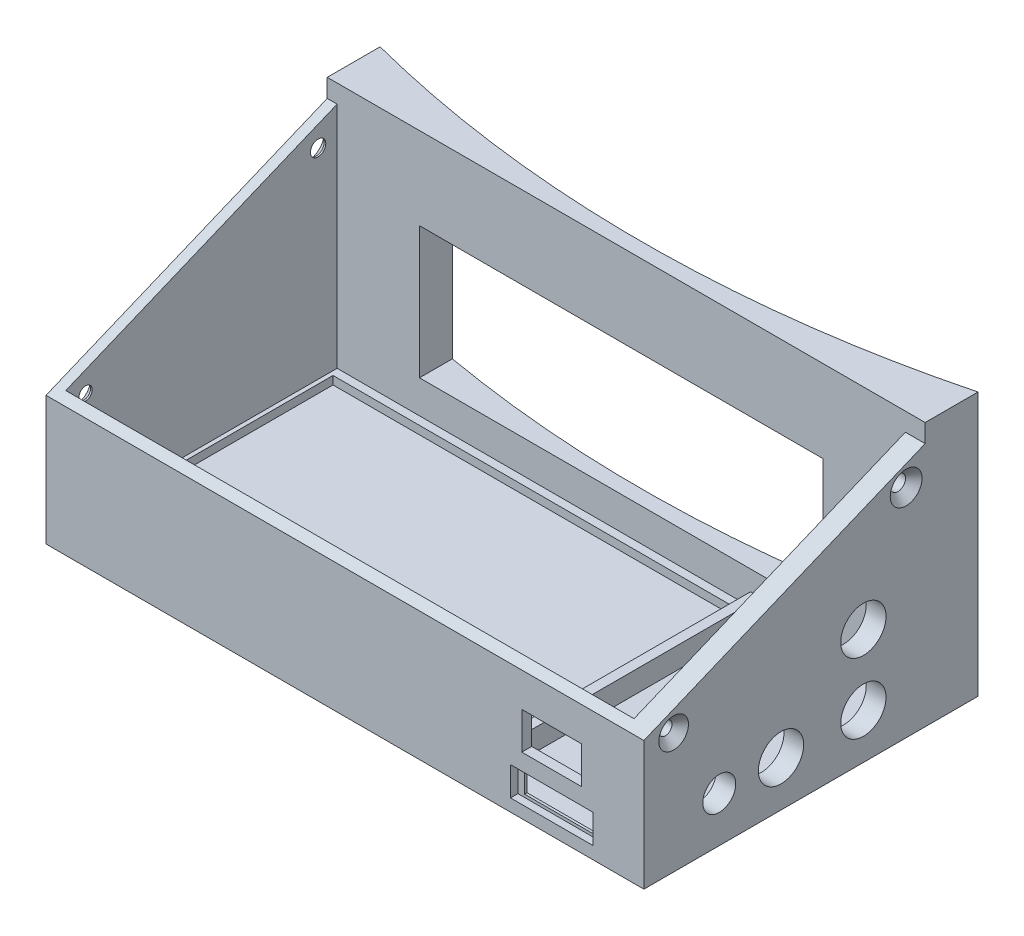
SolidWorks part; units mm, degrees
ref_plane "Ebene vorne" through (0, 0, 0) normal (0, 0, 1) x (1, 0, 0)
ref_plane "Ebene oben" through (0, 0, 0) normal (0, 1, 0) x (1, 0, 0)
ref_plane "Ebene rechts" through (0, 0, 0) normal (1, 0, 0) x (0, 0, -1)
sketch "Skizze1" plane through (0, 0, 0) normal (0, 1, 0) x (1, 0, 0)
  line L1 (0, 0) -> (145.2, 0)
  line L2 (0, 0) -> (0, 70.7)
  line L3 (0, 70.7) -> (145.2, 70.7)
  line L4 (145.2, 0) -> (145.2, 70.7)
  line L5 (0, 0) -> (145.2, 70.7) construction
  line L6 (0, 70.7) -> (145.2, 0) construction
  point P4 (72.6, 35.35)
  dimension "D1" = 145.2
  dimension "D2" = 70.7
extrude "Aufsatz-Linear austragen1" add sketch "Skizze1" along normal blind 64
sketch "Skizze3" plane through (0, 0, 0) normal (0, -1, 0) x (1, 0, 0)
  line L0 (0, -70.7) -> (145.2, -70.7)
  line L1 (145.2, -70.7) -> (145.2, -81.1345)
  line L2 (0, -70.7) -> (0, -81.1345)
  arc A0 (0, -81.1345) -> (145.2, -81.1345) centre (72.6, -361.9) cw
  point P8 (72.6, -71.9)
  point P10 (72.6, -70.7)
  dimension "D1" = 290
  dimension "D2" = 1.2
extrude "Aufsatz-Linear austragen2" add sketch "Skizze3" against normal up to vertex (64 mm away) up to point (145.2, 64, -70.7)
sketch "Skizze4" plane through (0, 0, 0) normal (0, -1, 0) x (1, 0, 0)
  line L0 (0, 0) -> (145.2, 0) construction
  line L1 (102.8, -2.4) -> (2.4, -2.4)
  line L2 (102.8, -2.4) -> (102.8, -68.3)
  line L3 (102.8, -68.3) -> (2.4, -68.3)
  line L4 (2.4, -2.4) -> (2.4, -68.3)
  line L5 (102.8, -2.4) -> (2.4, -68.3) construction
  line L6 (102.8, -68.3) -> (2.4, -2.4) construction
  line L8 (0, -81.1345) -> (0, 0) construction
  line L9 (145.2, 0) -> (145.2, -81.1345) construction
  line L10 (105.2, -2.4) -> (140.4, -2.4)
  line L11 (105.2, -2.4) -> (105.2, -68.3)
  line L12 (105.2, -68.3) -> (140.4, -68.3)
  line L13 (140.4, -2.4) -> (140.4, -68.3)
  line L14 (105.2, -2.4) -> (140.4, -68.3) construction
  line L15 (105.2, -68.3) -> (140.4, -2.4) construction
  point P4 (52.6, -35.35)
  point P13 (122.8, -35.35)
  dimension "D1" = 2.4
  dimension "D2" = 2.4
  dimension "D3" = 100.4
  dimension "D4" = 65.9
  dimension "D5" = 2.4
  dimension "D6" = 4.8
extrude "Schnitt-Linear austragen3" cut sketch "Skizze4" against normal through all
sketch "Skizze5" plane through (0, 0, 0) normal (0, -1, 0) x (1, 0, 0)
  line L1 (2.4, -2.4) -> (102.8, -2.4)
  line L2 (2.4, -2.4) -> (2.4, -68.3)
  line L3 (2.4, -68.3) -> (102.8, -68.3)
  line L4 (102.8, -2.4) -> (102.8, -68.3)
  line L5 (2.4, -2.4) -> (102.8, -68.3) construction
  line L6 (2.4, -68.3) -> (102.8, -2.4) construction
  line L7 (105.2, -2.4) -> (140.4, -2.4)
  line L8 (105.2, -2.4) -> (105.2, -68.3)
  line L9 (105.2, -68.3) -> (140.4, -68.3)
  line L10 (140.4, -2.4) -> (140.4, -68.3)
  line L11 (105.2, -2.4) -> (140.4, -68.3) construction
  line L12 (105.2, -68.3) -> (140.4, -2.4) construction
  point P4 (52.6, -35.35)
  point P11 (122.8, -35.35)
extrude "Aufsatz-Linear austragen3" add sketch "Skizze5" against normal blind 2 separate body
sketch "Skizze6" plane through (0, 2, 0) normal (0, 1, 0) x (1, 0, 0)
  line L1 (2.4, 68.3) -> (102.8, 68.3)
  line L2 (2.4, 68.3) -> (2.4, 2.4)
  line L3 (2.4, 2.4) -> (102.8, 2.4)
  line L4 (102.8, 68.3) -> (102.8, 2.4)
  line L5 (2.4, 68.3) -> (102.8, 2.4) construction
  line L6 (2.4, 2.4) -> (102.8, 68.3) construction
  line L7 (3.4, 66.3) -> (101.8, 66.3)
  line L8 (3.4, 66.3) -> (3.4, 4.4)
  line L9 (3.4, 4.4) -> (101.8, 4.4)
  line L10 (101.8, 66.3) -> (101.8, 4.4)
  line L11 (3.4, 66.3) -> (101.8, 4.4) construction
  line L12 (3.4, 4.4) -> (101.8, 66.3) construction
  point P4 (52.6, 35.35)
  point P11 (52.6, 35.35)
  dimension "D1" = 2
  dimension "D2" = 2
  dimension "D3" = 1
  dimension "D4" = 1
extrude "Aufsatz-Linear austragen4" add sketch "Skizze6" along normal blind 2
sketch "Skizze8" plane through (0, 64, 0) normal (0, 1, 0) x (1, 0, 0)
  line L1 (102.8, 68.3) -> (105.2, 68.3)
  line L2 (102.8, 68.3) -> (102.8, 2.4)
  line L3 (102.8, 2.4) -> (105.2, 2.4)
  line L4 (105.2, 68.3) -> (105.2, 2.4)
  line L5 (102.8, 68.3) -> (105.2, 2.4) construction
  line L6 (102.8, 2.4) -> (105.2, 68.3) construction
  point P4 (104, 35.35)
extrude "Schnitt-Linear austragen4" cut sketch "Skizze8" against normal offset from surface (56.8 mm away) 3.2 up to face at (52.6, 4, -35.35)
sketch "Skizze9" plane through (0, 0, 0) normal (-1, 0, 0) x (0, 0, 1)
  line L0 (-68.3, 64) -> (0, 64)
  line L1 (-81.1345, 64) -> (0, 64) construction
  line L2 (0, 64) -> (0, 0) construction
  line L3 (0, 64) -> (0, 35.7092)
  line L4 (0, 35.7092) -> (-68.3, 64)
  dimension "D1" = 22.5
extrude "Schnitt-Linear austragen5" cut sketch "Skizze9" against normal through all
sketch "Skizze10" plane through (0, 0, 0) normal (-1, 0, 0) x (0, 0, 1)
  line L0 (-68.3, 64) -> (0, 35.7092)
  line L1 (0, 35.7092) -> (0, 31.2714)
  line L2 (0, 35.7092) -> (0, 0) construction
  line L3 (0, 31.2714) -> (-68.3, 59.5622)
  line L4 (-68.3, 59.5622) -> (-68.3, 64)
  dimension "D1" = 4.1
extrude "Schnitt-Linear austragen6" cut sketch "Skizze10" against normal through all
sketch "Skizze11" plane through (0, 0, -68.3) normal (0, 0, 1) x (1, 0, 0)
  line L0 (2.4, 59.5622) -> (2.4, 4) construction
  line L1 (22.4, 44) -> (120.4, 44)
  line L2 (22.4, 44) -> (22.4, 12)
  line L3 (22.4, 12) -> (120.4, 12)
  line L4 (120.4, 44) -> (120.4, 12)
  line L5 (22.4, 44) -> (120.4, 12) construction
  line L6 (22.4, 12) -> (120.4, 44) construction
  line L7 (140.4, 59.5622) -> (140.4, 0) construction
  line L8 (0, 64) -> (145.2, 64) construction
  line L9 (105.2, 2) -> (140.4, 2) construction
  point P4 (71.4, 28)
  dimension "D1" = 20
  dimension "D2" = 20
  dimension "D3" = 20
  dimension "D4" = 10
extrude "Schnitt-Linear austragen7" cut sketch "Skizze11" against normal through all
sketch "Skizze12" plane through (0, 0, 0) normal (-1, 0, 0) x (0, 0, 1)
  line L0 (-68.3, 59.5622) -> (-59.0612, 55.7354) construction
  line L1 (-68.3, 59.5622) -> (0, 31.2714) construction
  line L2 (-59.0612, 55.7354) -> (-59.0612, 45.7354) construction
  line L3 (-59.0612, 45.7354) -> (-68.3, 49.5622) construction
  line L4 (-68.3, 49.5622) -> (-68.3, 59.5622) construction
  line L5 (-11.8388, 36.1752) -> (-2.6, 32.3484) construction
  line L6 (-2.6, 32.3484) -> (-2.6, 22.3484) construction
  line L7 (-2.6, 22.3484) -> (-11.8388, 26.1752) construction
  line L8 (-11.8388, 26.1752) -> (-11.8388, 36.1752) construction
  line L9 (0, 31.2714) -> (0, 0) construction
  line L10 (-11.8388, 36.1752) -> (-2.6, 22.3484) construction
  line L11 (-2.6, 22.3484) -> (-11.8388, 26.1752) construction
  line L12 (-11.8388, 26.1752) -> (-2.6, 32.3484) construction
  line L13 (-68.3, 59.5622) -> (-59.0612, 45.7354) construction
  line L14 (-59.0612, 45.7354) -> (-68.3, 49.5622) construction
  line L15 (-68.3, 49.5622) -> (-59.0612, 55.7354) construction
  circle A0 centre (-63.6806, 52.6488) radius 1.8629
  circle A1 centre (-7.2194, 29.2618) radius 1.6
  dimension "D3" = 3.2
  dimension "D1" = 10
  dimension "D2" = 2.6
extrude "Schnitt-Linear austragen8" cut sketch "Skizze12" against normal through all
chamfer "Fase1" distance 2 angle 45 4 edges at (145.2, 52.6488, -61.8177) (145.2, 29.2618, -5.6194) (0, 29.2618, -5.6194) (0, 52.6488, -61.8177)
sketch "Skizze13" plane through (145.2, 0, 0) normal (1, 0, 0) x (0, 0, -1)
  line L0 (68.3, 59.5622) -> (68.3, 0) construction
  line L1 (68.3, 2) -> (2.4, 2) construction
  circle A0 centre (53.3, 11) radius 5.5
  circle A1 centre (53.3, 28) radius 5.5
  circle A2 centre (33.3, 11) radius 5.5
  circle A3 centre (18.3, 11) radius 4
  point P12 (0, 0)
  point P13 (0, 0)
  point P14 (41.6627, 13.5532)
  point P15 (41.6931, 22.3748)
  point P16 (54.591, 16.0612)
  point P17 (41.0316, 36.798)
  point P18 (0, 0)
  point P19 (0, 0)
  dimension "D1" = 8
  dimension "D2" = 11
  dimension "D3" = 15
  dimension "D4" = 9
  dimension "D5" = 15
  dimension "D6" = 20
  dimension "D7" = 17
extrude "Schnitt-Linear austragen9" cut sketch "Skizze13" against normal up to surface (4.8 mm away) up to face at (140.4, 52.6488, -65.5435)
sketch "Skizze14" plane through (0, 0, 0) normal (0, 0, 1) x (1, 0, 0)
  line L0 (140.4, 2) -> (105.2, 2) construction
  line L1 (112.8, 10) -> (132.8, 10)
  line L2 (112.8, 10) -> (112.8, 3)
  line L3 (112.8, 3) -> (132.8, 3)
  line L4 (132.8, 10) -> (132.8, 3)
  line L5 (112.8, 10) -> (132.8, 3) construction
  line L6 (112.8, 3) -> (132.8, 10) construction
  line L7 (140.4, 32.2655) -> (140.4, 0) construction
  point P4 (122.8, 6.5)
  dimension "D1" = 20
  dimension "D2" = 7
  dimension "D3" = 1
  dimension "D4" = 17.6
extrude "Schnitt-Linear austragen10" cut sketch "Skizze14" against normal blind 1.8
sketch "Skizze15" plane through (0, 0, -1.8) normal (0, 0, 1) x (1, 0, 0)
  line L0 (112.8, 10) -> (112.8, 3) construction
  line L1 (114.4, 3.7) -> (131.2, 3.7)
  line L2 (114.4, 3.7) -> (114.4, 9)
  line L3 (114.4, 9) -> (131.2, 9)
  line L4 (131.2, 3.7) -> (131.2, 9)
  line L5 (114.4, 3.7) -> (131.2, 9) construction
  line L6 (114.4, 9) -> (131.2, 3.7) construction
  line L7 (132.8, 3) -> (132.8, 10) construction
  line L8 (112.8, 3) -> (132.8, 3) construction
  line L9 (132.8, 10) -> (112.8, 10) construction
  point P4 (122.8, 6.35)
  dimension "D1" = 1.6
  dimension "D2" = 1.6
  dimension "D3" = 0.7
  dimension "D4" = 1
extrude "Schnitt-Linear austragen11" cut sketch "Skizze15" against normal up to surface (0.6 mm away) up to face at (87.7, 10.8664, -2.4)
sketch "Skizze16" plane through (0, 0, 0) normal (0, 0, 1) x (1, 0, 0)
  line L0 (132.8, 10) -> (112.8, 10) construction
  line L1 (115.55, 23) -> (130.05, 23)
  line L2 (115.55, 23) -> (115.55, 14)
  line L3 (115.55, 14) -> (130.05, 14)
  line L4 (130.05, 23) -> (130.05, 14)
  line L5 (115.55, 23) -> (130.05, 14) construction
  line L6 (115.55, 14) -> (130.05, 23) construction
  line L7 (140.4, 32.2655) -> (140.4, 0) construction
  point P4 (122.8, 18.5)
  point P5 (122.827, 17.0412)
  dimension "D1" = 9
  dimension "D2" = 14.5
  dimension "D3" = 4
  dimension "D4" = 17.6
extrude "Schnitt-Linear austragen12" cut sketch "Skizze16" against normal up to surface (2.4 mm away) up to face at (122.8, 6.35, -2.4)
